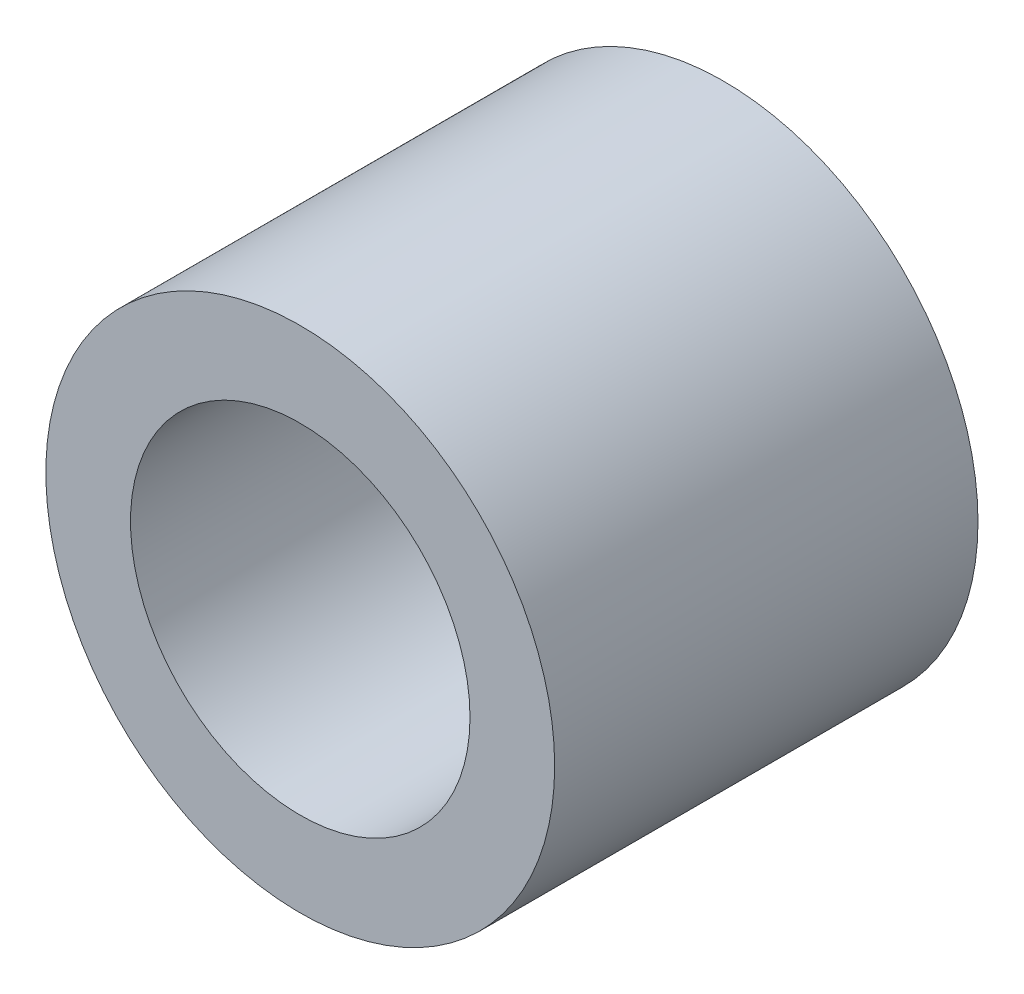
SolidWorks part; units mm, degrees
ref_plane "정면" through (0, 0, 0) normal (0, 0, 1) x (1, 0, 0)
ref_plane "윗면" through (0, 0, 0) normal (0, 1, 0) x (1, 0, 0)
ref_plane "우측면" through (0, 0, 0) normal (1, 0, 0) x (0, 0, -1)
sketch "스케치1" plane through (0, 0, 0) normal (0, 0, 1) x (1, 0, 0)
  circle A0 centre (0, 0) radius 20.05
  circle A1 centre (0, 0) radius 30.05
  dimension "D1" = 40.1
  dimension "D2" = 10
extrude "보스-돌출1" add sketch "스케치1" along normal blind 50
